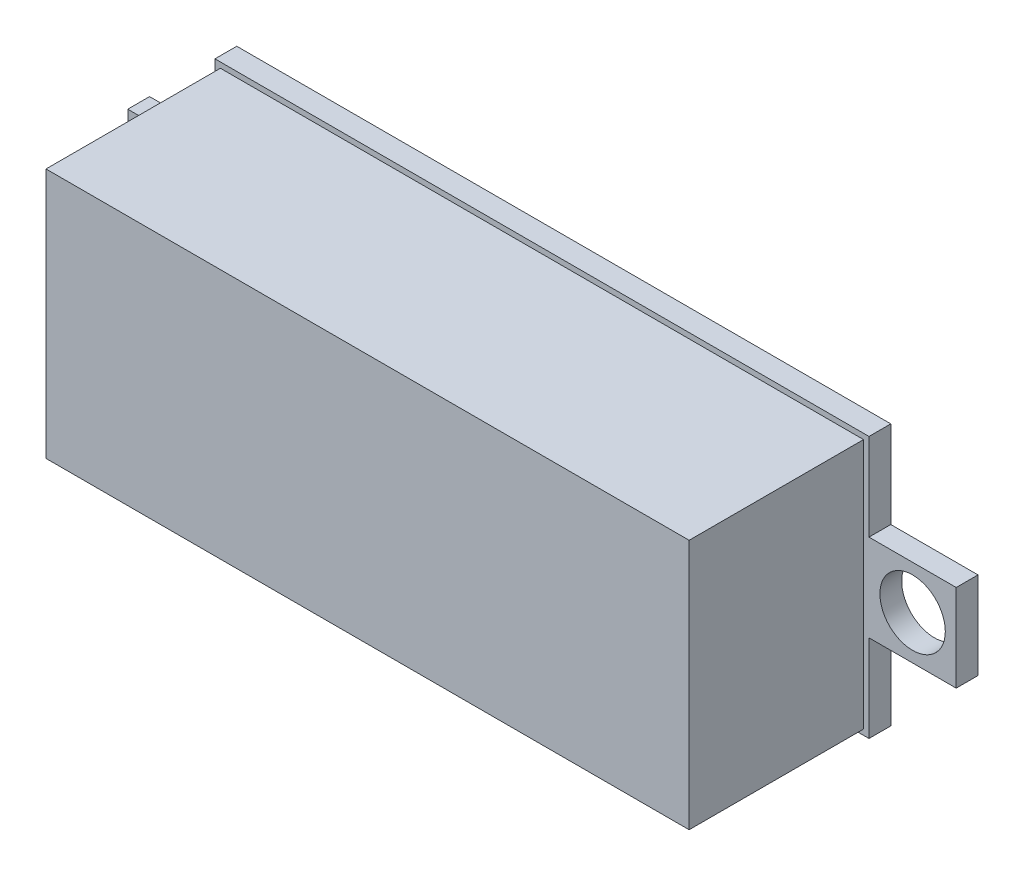
SolidWorks part; units mm, degrees
ref_plane "Piano frontale" through (0, 0, 0) normal (0, 0, 1) x (1, 0, 0)
ref_plane "Piano superiore" through (0, 0, 0) normal (0, 1, 0) x (1, 0, 0)
ref_plane "Piano destro" through (0, 0, 0) normal (1, 0, 0) x (0, 0, -1)
sketch "Schizzo1" plane through (0, 0, 0) normal (0, 0, 1) x (1, 0, 0)
  line L1 (0, 12) -> (30, 12)
  line L2 (0, 12) -> (0, 0)
  line L3 (0, 0) -> (30, 0)
  line L4 (30, 12) -> (30, 0)
  line L5 (-4, 8) -> (0, 8)
  line L6 (-4, 8) -> (-4, 4)
  line L7 (-4, 4) -> (0, 4)
  line L8 (0, 8) -> (0, 4)
  line L9 (30, 8) -> (34, 8)
  line L10 (30, 8) -> (30, 4)
  line L11 (30, 4) -> (34, 4)
  line L12 (34, 8) -> (34, 4)
  circle A0 centre (-2, 6) radius 1.5
  circle A1 centre (32, 6) radius 1.5
  dimension "D7" = 3
  dimension "D8" = 3
  dimension "D9" = 2
  dimension "D10" = 2
  dimension "D11" = 2
  dimension "D1" = 30
  dimension "D2" = 12
  dimension "D3" = 4
  dimension "D4" = 4
  dimension "D5" = 4
  dimension "D6" = 2
  dimension "D12" = 4
extrude "Estrusione-Estrusione1" add sketch "Schizzo1" along normal blind 1 contours L6 L7 L2 L5 A0 | L4 L1 L2 L3 | L12 L9 L4 L11 A1
sketch "Schizzo2" plane through (0, 0, 1) normal (0, 0, 1) x (1, 0, 0)
  line L0 (0, 12) -> (0, 8) construction
  line L1 (0.25, 11.75) -> (29.75, 11.75)
  line L2 (0.25, 11.75) -> (0.25, 0.25)
  line L3 (0.25, 0.25) -> (29.75, 0.25)
  line L4 (29.75, 11.75) -> (29.75, 0.25)
  line L5 (0, 12) -> (30, 12) construction
  dimension "D1" = 29.5
  dimension "D2" = 11.5
  dimension "D3" = 0.25
  dimension "D4" = 0.25
extrude "Estrusione-Estrusione2" add sketch "Schizzo2" along normal blind 8
